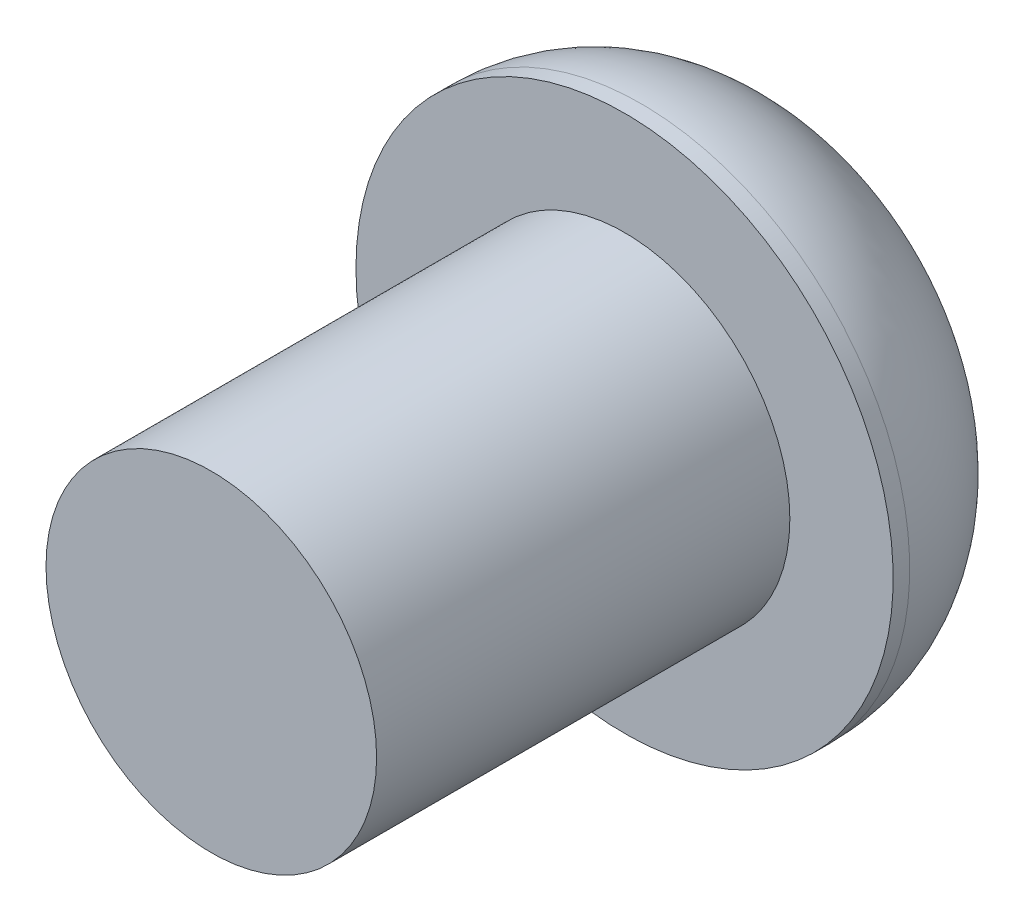
SolidWorks part; units mm, degrees
ref_plane "前视基准面" through (0, 0, 0) normal (0, 0, 1) x (1, 0, 0)
ref_plane "上视基准面" through (0, 0, 0) normal (0, 1, 0) x (1, 0, 0)
ref_plane "右视基准面" through (0, 0, 0) normal (1, 0, 0) x (0, 0, -1)
sketch "草图1" plane through (0, 0, 0) normal (0, 0, 1) x (1, 0, 0)
  circle A0 centre (0, 0) radius 2
  dimension "D1" = 4
extrude "凸台-拉伸1" add sketch "草图1" along normal blind 5
sketch "草图2" plane through (0, 0, 0) normal (0, 0, -1) x (-1, 0, 0)
  circle A0 centre (0, 0) radius 3.25
  dimension "D1" = 6.5
extrude "凸台-拉伸2" add sketch "草图2" along normal blind 2.2
fillet "圆角1" radius 2 1 edges at (-3.25, 0, -2.2)
sketch "草图3" plane through (0, 0, -2.2) normal (0, 0, -1) x (-1, 0, 0)
  line L0 (0, 3.24) -> (0, -3.24) construction
  line L1 (-3.24, 0) -> (3.24, 0) construction
  line L2 (-3.24, 0.25) -> (3.24, 0.25) construction
  line L3 (0.25, 3.24) -> (0.25, -3.24) construction
  line L4 (-3.24, -0.25) -> (3.24, -0.25) construction
  line L5 (-0.25, 3.24) -> (-0.25, -3.24) construction
  line L7 (3.24, 0.25) -> (3.24, -0.25)
  line L8 (-0.25, 3.24) -> (0.25, 3.24)
  line L10 (-0.25, 3.24) -> (-0.25, 0.25)
  line L11 (0.25, 3.24) -> (0.25, 0.25)
  line L12 (3.24, 0.25) -> (0.25, 0.25)
  line L13 (3.24, -0.25) -> (0.25, -0.25)
  line L15 (0.25, -3.24) -> (0.25, -0.25)
  line L16 (-0.25, -3.24) -> (-0.25, -0.25)
  line L17 (0.25, -3.24) -> (-0.25, -3.24)
  line L18 (-3.24, -0.25) -> (-0.25, -0.25)
  line L19 (-3.24, 0.25) -> (-0.25, 0.25)
  line L20 (-3.24, -0.25) -> (-3.24, 0.25)
  line L21 (3.24, 0.25) -> (3.24, -0.25) [skipped]
  circle A1 centre (0, 0) radius 3.24 construction
  dimension "D1" = 0.25
  dimension "D2" = 0.25
  dimension "D3" = 4
extrude "切除-拉伸1" cut sketch "草图3" against normal blind 0.5
